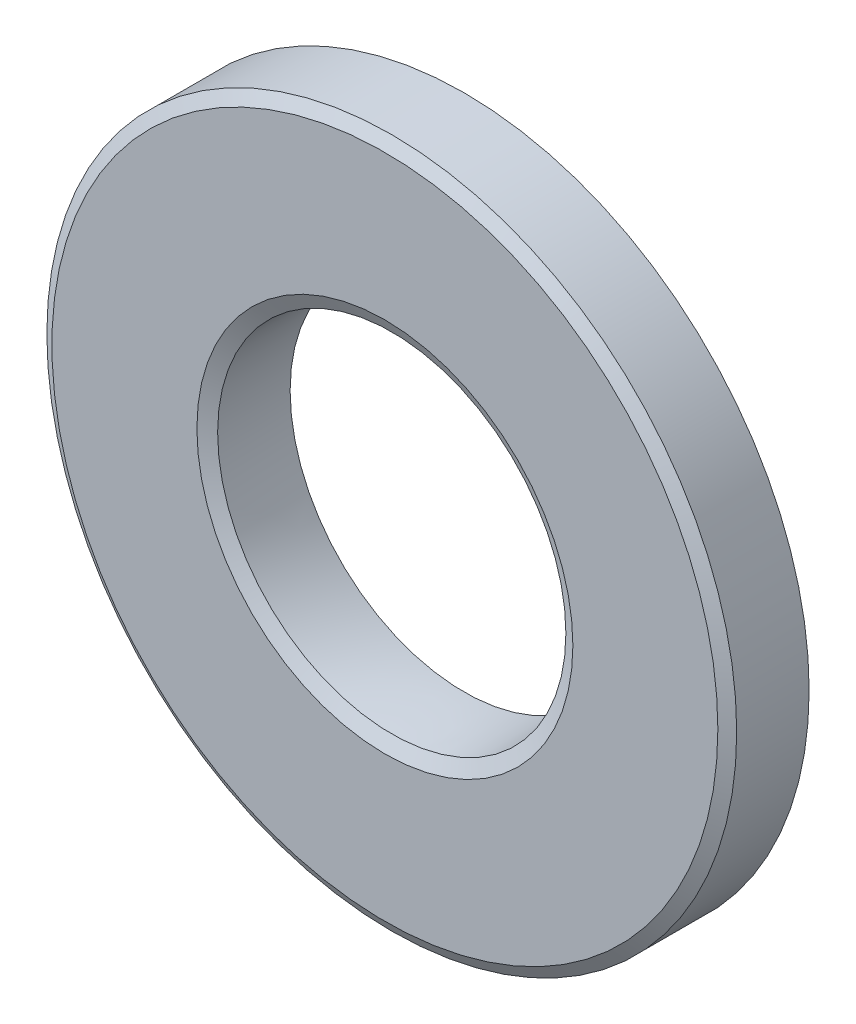
SolidWorks part; units mm, degrees
other "Imported1" parameters "D1"=0.254
ref_plane "Front Plane" through (0, 0, 0) normal (0, 0, 1) x (1, 0, 0)
ref_plane "Top Plane" through (0, 0, 0) normal (0, 1, 0) x (1, 0, 0)
ref_plane "Right Plane" through (0, 0, 0) normal (1, 0, 0) x (0, 0, -1)
sketch "Sketch1" plane through (0, 0, 0) normal (0, 0, 1) x (1, 0, 0)
  line L0 (-12.7, 0) -> (12.7, 0) construction
  line L1 (-6.3754, 0) -> (6.3754, 0) construction
  circle A0 centre (0, 0) radius 6.3754 construction
  circle A1 centre (0, 0) radius 12.7 construction
  point P8 (0, 0)
  point P9 (0, 12.7)
  point P11 (6.3754, 0)
  dimension "ID" = 12.7508
  dimension "OD" = 25.4
sketch "Sketch2" plane through (0, 0, 0) normal (1, 0, 0) x (0, 0, -1)
  line L0 (-1.5875, 12.7) -> (1.5875, 12.7) construction
  point P2 (0, 12.7)
  dimension "Thickness" = 3.175
sketch "Sketch3" plane through (0, 0, 0) normal (0, 0, 1) x (1, 0, 0)
  circle A0 centre (0, 0) radius 6.3754
  circle A1 centre (0, 0) radius 12.7
extrude "Boss-Extrude1" add sketch "Sketch3" along normal up to vertex (1.5875 mm away) and the other way up to vertex (1.5875 mm away) up to point (0, 12.7, 1.5875) other way up to point (0, 12.7, -1.5875)
chamfer "Chamfer1" distance 0.254 angle 60 2 edges at (12.7, 0, -1.5875) (12.7, 0, 1.5875)
sketch "Sketch4" plane through (0, 0, 0) normal (1, 0, 0) x (0, 0, -1)
  line L3 (-1.5875, 6.3246) -> (-1.5875, 6.4262)
  line L4 (-1.5875, 6.3246) -> (1.5875, 6.3246)
  line L5 (1.5875, 6.3246) -> (1.5875, 6.4262)
  line L6 (-1.5875, 0) -> (1.5875, 0) construction
  arc A0 (-1.5875, 6.4262) -> (1.5875, 6.4262) centre (0, 31.2055) ccw
  point P0 (0, 6.3754)
  point P9 (-1.5875, 6.3754)
  point P13 (0, 0)
  dimension "D1" = 0.0508
revolve "Cut-Revolve1" cut sketch "Sketch4" angle 360 about L6
chamfer "Chamfer2" distance 0.254 angle 60 2 edges at (0, -6.4262, -1.5875) (0, -6.4262, 1.5875)
equation "\"D1@Chamfer2\"=\"D1@Chamfer1\""
